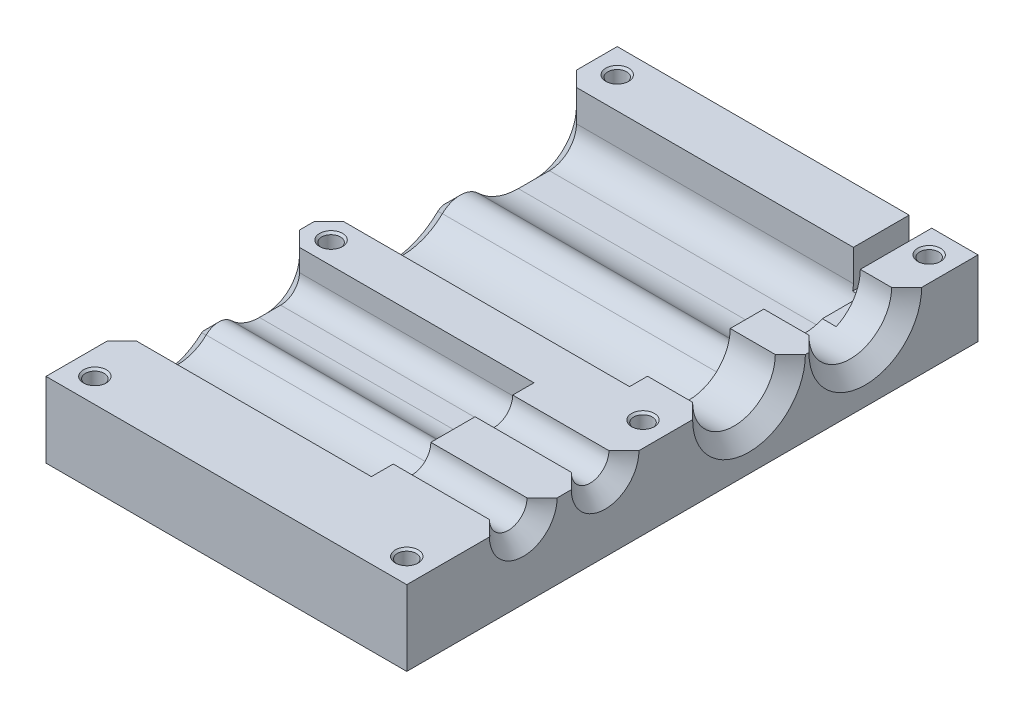
SolidWorks part; units mm, degrees
material "POM Acetal Copolymer"
ref_plane "Front Plane" through (0, 0, 0) normal (0, 0, 1) x (1, 0, 0)
ref_plane "Top Plane" through (0, 0, 0) normal (0, 1, 0) x (1, 0, 0)
ref_plane "Right Plane" through (0, 0, 0) normal (1, 0, 0) x (0, 0, -1)
sketch "Sketch1" plane through (0, 0, 0) normal (0, 1, 0) x (1, 0, 0)
  line L0 (-24, 38) -> (-24, -38)
  line L1 (-24, 38) -> (24, 38)
  line L2 (-24, -38) -> (24, -38)
  line L3 (24, 38) -> (24, -38)
  line L4 (-24, 38) -> (24, -38) construction
  line L5 (-24, -38) -> (24, 38) construction
  point P1 (0, 0)
  dimension "D1" = 48
  dimension "D2" = 76
extrude "Boss-Extrude1" add sketch "Sketch1" along normal blind 10
sketch "Sketch2" plane through (-24, 0, 0) normal (-1, 0, 0) x (0, 0, 1)
  line L1 (-38, 10) -> (38, 10) construction
  circle A0 centre (-23, 10) radius 5.5
  circle A1 centre (-7.5312, 10) radius 5.5
  circle A2 centre (11.6088, 10) radius 2.5
  circle A3 centre (22.5, 10) radius 2.5
  dimension "D1" = 5
  dimension "D2" = 11
  dimension "D3" = 10.8912
  dimension "D4" = 15.4688
  dimension "D5" = 15
  dimension "D6" = 15.5
extrude "Cut-Extrude1" cut sketch "Sketch2" against normal through all
sketch "Sketch3" plane through (-24, 0, 0) normal (-1, 0, 0) x (0, 0, 1)
  line L0 (-30.5756, 16.8073) -> (-30.5756, 2.2109)
  line L1 (-30.5756, 2.2109) -> (-22.8406, 2.2109)
  line L2 (6.2785, 18.1956) -> (6.2785, 4.5924)
  line L3 (6.2785, 4.5924) -> (11.6088, 4.5924)
  line L4 (-30.5756, 16.8073) -> (-10.9415, 16.8073)
  line L5 (6.2785, 18.1956) -> (17.5158, 12.3171)
  line L6 (-5.0505, 16.8073) -> (-26.9356, 16.8073) construction
  line L7 (-30.5756, 5.8509) -> (-30.5756, 13.1673) construction
  line L8 (6.2785, 12.921) -> (6.2785, 7.7701) construction
  arc A0 (18.691, 6.109) -> (17.5158, 12.3171) centre (22.4616, 10.0381) ccw
  arc A1 (-12.7389, 4.3772) -> (-10.9415, 16.8073) centre (-7.3706, 9.9459) ccw
  arc A2 (-22.8406, 2.2109) -> (-17.4723, 4.3772) centre (-22.8406, 9.9459) ccw
  arc A3 (-17.4723, 4.3772) -> (-12.7389, 4.3772) centre (-15.1056, 1.9222) cw
  arc A4 (-16.1312, 8.6953) -> (-17.5589, 14.2684) centre (-22.8406, 9.9459) ccw construction
  arc A7 (-12.7377, 4.376) -> (-2.7067, 16.1167) centre (-7.3706, 9.9459) ccw construction
  arc A9 (11.6088, 4.5924) -> (15.3606, 6.1058) centre (11.6088, 10) ccw
  arc A10 (15.3606, 6.1058) -> (18.691, 6.109) centre (17.0275, 4.3756) cw
  arc A12 (25.7451, 5.6937) -> (18.683, 13.9594) centre (22.4616, 10.0381) ccw construction
  arc A13 (15.349, 13.9594) -> (18.683, 13.9594) centre (17.016, 15.6894) ccw construction
  arc A14 (9.1088, 10) -> (14.1088, 10) centre (11.6088, 10) ccw construction
  dimension "D1" = 3.41
extrude "Cut-Extrude2" cut sketch "Sketch3" against normal blind 40
fillet "Fillet1" radius 3.6 1 edges at (-4, 2.2109, -30.5756)
fillet "Fillet2" radius 2.5 1 edges at (-4, 4.5924, 6.2785)
hole_wizard "M3 Tapped Hole1" positions "Sketch5" profile "Sketch4" tap size "M3" standard "ISO" end condition through all
sketch "Sketch5" plane through (0, 10, 0) normal (0, 1, 0) x (1, 0, 0)
  line L0 (20.75, -3.3214) -> (-20.75, -3.3214) construction
  line L2 (-24, -38) -> (24, -38) construction
  line L3 (24, -38) -> (24, -25) construction
  line L4 (24, 38) -> (-24, 38) construction
  line L5 (-24, 38) -> (-24, 30.5756) construction
  line L6 (-20.75, -3.3214) -> (-24, -3.3214) construction
  line L7 (-24, -0.3642) -> (-24, -6.2785) construction
  circle A1 centre (20.75, -34.75) radius 3.25 construction
  circle A3 centre (-20.75, 34.75) radius 3.25 construction
  point P0 (-20.75, 34.75)
  point P2 (20.75, 34.75)
  point P4 (20.75, -3.3214)
  point P6 (-20.75, -3.3214)
  point P8 (-20.75, -34.75)
  point P10 (20.75, -34.75)
  dimension "D1" = 6.5
sketch "Sketch4" plane through (-20.75, 10, -34.75) normal (1, 0, 0) x (0, 0, 1)
  line L0 (0, 0) -> (0, 10)
  line L1 (0, 10) -> (1.25, 10)
  line L2 (1.25, 10) -> (1.25, 0.275)
  line L3 (1.25, 0.275) -> (1.525, 0)
  line L5 (1.525, 0) -> (0, 0)
  line L6 (-1.25, 0.275) -> (-1.525, 0) construction
  line L11 (0, -6.35) -> (0, 107.95) construction
  dimension "Thread Major Dia." = 2.5
  dimension "Thru Tap Drill Depth" = 10
  dimension "Near C'Sink Dia." = 3.05
  dimension "Near C'Sink Angle" = 90
chamfer "Chamfer1" distance 2 angle 45 12 edges at (-24, 8.5462, 6.2785) (-24, 5.3247, 7.0107) (-24, 5.0212, 24.5797) (-24, 4.5924, 10.1936) (-24, 6.7781, 17.0252) (-24, 4.985, 13.6315) (-24, 7.9055, -30.5756) (-24, 3.2653, -29.5212) (-24, 2.8378, -4.3203) (-24, 2.2109, -24.9081) (-24, 5.3322, -15.1056) (-24, 2.7729, -19.9461)
sketch "Sketch6" plane through (16, 0, 0) normal (-1, 0, 0) x (0, 0, 1)
  line L5 (6.2785, 10) -> (6.2785, 7.0924)
  line L6 (8.7785, 4.5924) -> (11.6088, 4.5924)
  line L7 (27.9071, 10) -> (25, 10)
  line L8 (20, 10) -> (14.1088, 10)
  line L9 (9.1088, 10) -> (6.2785, 10)
  line L10 (6.2785, 10) -> (6.2785, 7.0924)
  line L11 (8.7785, 4.5924) -> (11.6088, 4.5924)
  line L12 (27.9071, 10) -> (25, 10)
  line L13 (20, 10) -> (14.1088, 10)
  line L14 (9.1088, 10) -> (6.2785, 10)
  arc A6 (6.2785, 7.0924) -> (8.7785, 4.5924) centre (8.7785, 7.0924) ccw
  arc A7 (11.6088, 4.5924) -> (15.3606, 6.1058) centre (11.6088, 10) ccw
  arc A8 (18.691, 6.109) -> (15.3606, 6.1058) centre (17.0275, 4.3756) ccw
  arc A9 (18.691, 6.109) -> (27.9071, 10) centre (22.4616, 10.0381) ccw
  arc A10 (20, 10) -> (25, 10) centre (22.5, 10) ccw
  arc A11 (9.1088, 10) -> (14.1088, 10) centre (11.6088, 10) ccw
  arc A12 (6.2785, 7.0924) -> (8.7785, 4.5924) centre (8.7785, 7.0924) ccw
  arc A13 (11.6088, 4.5924) -> (15.3606, 6.1058) centre (11.6088, 10) ccw
  arc A14 (18.691, 6.109) -> (15.3606, 6.1058) centre (17.0275, 4.3756) ccw
  arc A15 (18.691, 6.109) -> (27.9071, 10) centre (22.4616, 10.0381) ccw
  arc A16 (20, 10) -> (25, 10) centre (22.5, 10) ccw
  arc A17 (9.1088, 10) -> (14.1088, 10) centre (11.6088, 10) ccw
  dimension "D1" = 0
extrude "Boss-Extrude2" add sketch "Sketch6" along normal blind 6.8
chamfer "Chamfer2" distance 2 angle 45 4 edges at (24, 7.5, 22.5) (24, 7.5, 11.6088) (24, 4.5, -7.5312) (24, 4.5, -23)
sketch "Sketch7" plane through (0, 10, 0) normal (0, 1, 0) x (1, 0, 0)
  line L1 (17.842, 24.0424) -> (14.842, 24.0424)
  line L2 (17.842, 24.0424) -> (17.842, 42.5657)
  line L3 (17.842, 42.5657) -> (14.842, 42.5657)
  line L4 (14.842, 24.0424) -> (14.842, 42.5657)
  line L6 (-24, 38) -> (-24, 32.5756) construction
  dimension "D1" = 3
  dimension "D2" = 38.842
extrude "Cut-Extrude3" cut sketch "Sketch7" against normal blind 5
